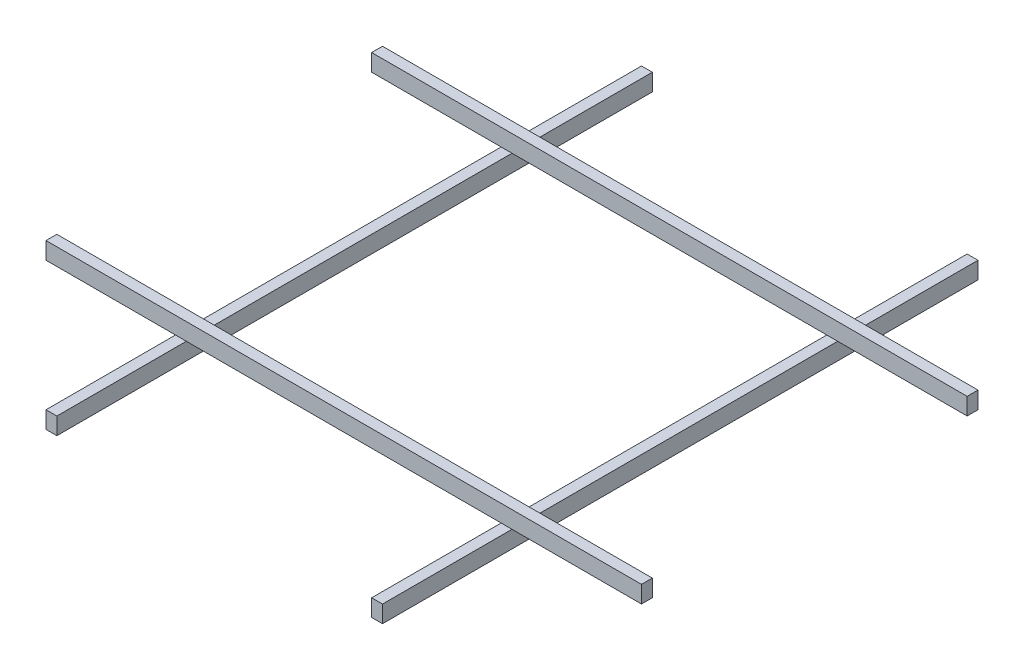
SolidWorks part; units mm, degrees
material "Doug Fir"
ref_plane "Front Plane" through (0, 0, 0) normal (0, 0, 1) x (1, 0, 0)
ref_plane "Top Plane" through (0, 0, 0) normal (0, 1, 0) x (1, 0, 0)
ref_plane "Right Plane" through (0, 0, 0) normal (1, 0, 0) x (0, 0, -1)
sketch "Lower Level" plane through (0, 0, 0) normal (0, 1, 0) x (1, 0, 0)
  line L0 (800.1, 0) -> (800.1, 4876.8)
  line L1 (3467.1, 0) -> (3467.1, 4876.8)
  line L2 (800.1, 2438.4) -> (3467.1, 2438.4) construction
  point P7 (2133.6, 2438.4)
  dimension "D1" = 4876.8
  dimension "D2" = 1333.5
ref_plane "Plane2" through (0, 139.7, 0) normal (0, 1, 0) x (1, 0, 0)
sketch "Sketch12" plane through (0, 139.7, 0) normal (0, 1, 0) x (1, 0, 0)
  line L0 (-304.8, 3771.9) -> (4572, 3771.9)
  line L1 (4572, 1104.9) -> (-304.8, 1104.9)
  line L2 (2133.6, 3771.9) -> (2133.6, 1104.9) construction
  point P0 (2133.6, 2438.4)
  point P6 (2133.6, 1104.9)
  point P7 (2133.6, 3771.9)
  point P10 (2133.6, 2438.4)
  dimension "D1" = 4876.8
  dimension "D2" = 1333.5
other "Profiles 4X6(1)"
ref_plane "Plane1" through (800.1, 0, 0) normal (0, 0, -1) x (-1, 0, 0)
sketch "Sketch1" plane through (800.1, 0, 0) normal (0, 0, -1) x (-1, 0, 0)
  line L1 (-44.45, 69.85) -> (44.45, 69.85)
  line L2 (-44.45, 69.85) -> (-44.45, -69.85)
  line L3 (-44.45, -69.85) -> (44.45, -69.85)
  line L4 (44.45, 69.85) -> (44.45, -69.85)
  line L5 (-44.45, 69.85) -> (44.45, -69.85) construction
  line L6 (-44.45, -69.85) -> (44.45, 69.85) construction
  point P0 (0, 0)
  point P6 (0, 69.85)
  point P7 (0, -69.85)
  point P8 (44.45, 0)
  point P9 (-44.45, 0)
  point P10 (0, 0)
  dimension "D1" = 88.9
  dimension "D2" = 139.7
sketch3d "3DSketch2"
  line L0 (2133.6, 139.7, -2438.4) -> (2133.6, 0, -2438.4)
  line L1 (800.1, 0, -2438.4) -> (3467.1, 0, -2438.4) construction
equation "\"Width\" = 52.5"
equation "\"Length\"=192"
equation "\"D1@Lower Level\"=\"Length\""
equation "\"D2@Lower Level\"=\"Width\""
equation "\"D1@Sketch12\"=\"Length\""
equation "\"D2@Sketch12\"=\"Width\""
